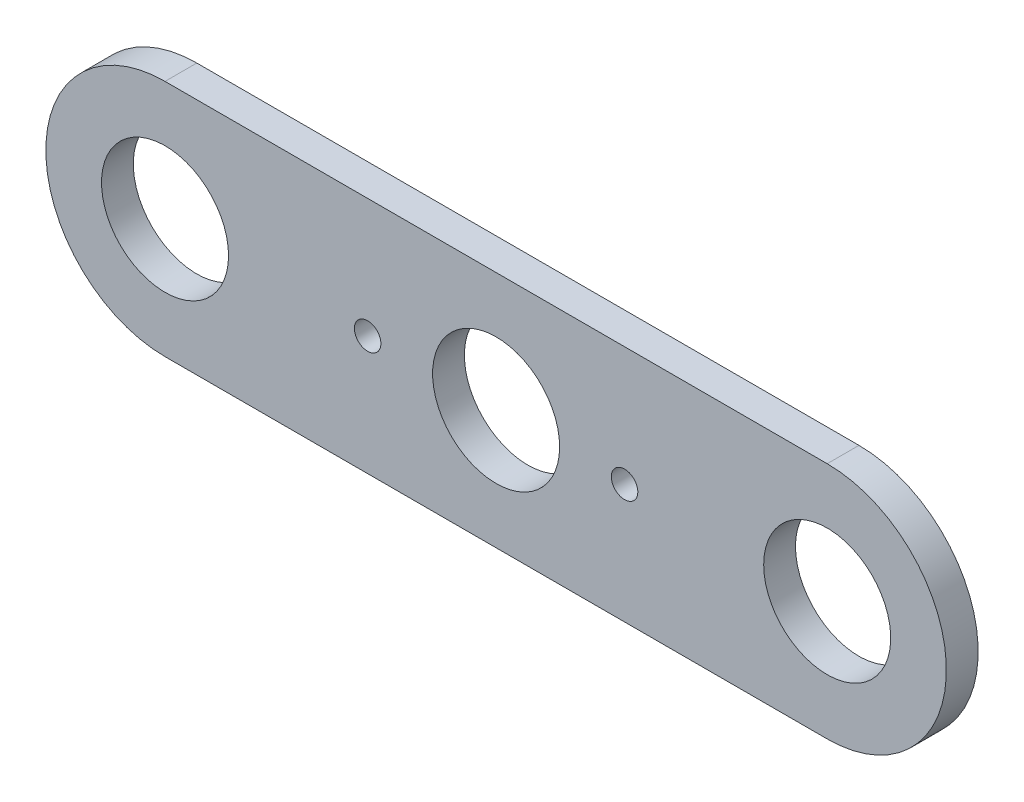
SolidWorks part; units mm, degrees
ref_plane "Front Plane" through (0, 0, 0) normal (0, 0, 1) x (1, 0, 0)
ref_plane "Top Plane" through (0, 0, 0) normal (0, 1, 0) x (1, 0, 0)
ref_plane "Right Plane" through (0, 0, 0) normal (1, 0, 0) x (0, 0, -1)
sketch "Sketch2" plane through (0, 0, 0) normal (0, 0, 1) x (1, 0, 0)
  line L0 (0, 22.5) -> (0, -22.5) construction
  line L1 (-62.5, -22.5) -> (62.5, -22.5)
  line L3 (-62.5, 22.5) -> (62.5, 22.5)
  line L5 (-62.5, -22.5) -> (62.5, 22.5) construction
  line L6 (-62.5, 22.5) -> (62.5, -22.5) construction
  arc A0 (62.5, -22.5) -> (62.5, 22.5) centre (62.5, 0) ccw
  arc A1 (-62.5, -22.5) -> (-62.5, 22.5) centre (-62.5, 0) cw
  circle A2 centre (-62.5, 0) radius 11.99
  circle A4 centre (62.5, 0) radius 11.99
  circle A5 centre (0, 0) radius 11.99
  point P0 (0, 0)
  dimension "D3" = 23.98
  dimension "D4" = 23.98
  dimension "D1" = 45
  dimension "D2" = 125
extrude "Boss-Extrude1" add sketch "Sketch2" along normal blind 6
sketch "Sketch3" plane through (0, 0, 6) normal (0, 0, 1) x (1, 0, 0)
  line L0 (-62.5, 0) -> (0, 0) construction
  line L1 (0, -1000) -> (0, 49000) construction
  circle A0 centre (-24.25, 0) radius 2.5
  circle A1 centre (24.25, 0) radius 2.5
  dimension "D1" = 5
  dimension "D2" = 24.25
extrude "Cut-Extrude1" cut sketch "Sketch3" against normal blind 10
